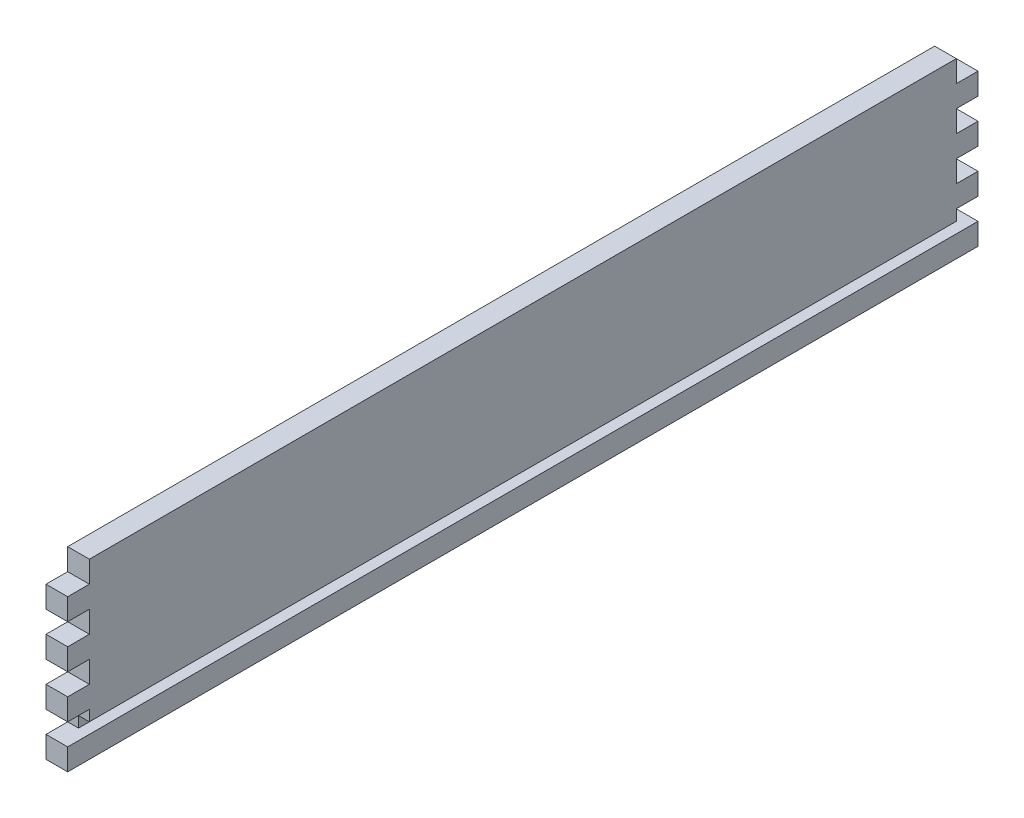
SolidWorks part; units mm, degrees
ref_plane "Front Plane" through (0, 0, 0) normal (0, 0, 1) x (1, 0, 0)
ref_plane "Top Plane" through (0, 0, 0) normal (0, 1, 0) x (1, 0, 0)
ref_plane "Right Plane" through (0, 0, 0) normal (1, 0, 0) x (0, 0, -1)
sketch "Sketch1" plane through (0, 0, 0) normal (1, 0, 0) x (0, 0, -1)
  line L0 (12.7, 101.6) -> (12.7, 88.9)
  line L1 (0, 0) -> (533.4, 0)
  line L2 (0, 0) -> (0, 12.7)
  line L3 (12.7, 101.6) -> (520.7, 101.6)
  line L4 (533.4, 0) -> (533.4, 12.7)
  line L5 (12.7, 88.9) -> (0, 88.9)
  line L6 (12.7, 76.2) -> (0, 76.2)
  line L8 (12.7, 63.5) -> (0, 63.5)
  line L9 (12.7, 76.2) -> (12.7, 63.5)
  line L10 (12.7, 50.8) -> (0, 50.8)
  line L12 (12.7, 38.1) -> (0, 38.1)
  line L13 (12.7, 50.8) -> (12.7, 38.1)
  line L14 (12.7, 25.4) -> (0, 25.4)
  line L16 (12.7, 12.7) -> (0, 12.7)
  line L17 (12.7, 25.4) -> (12.7, 12.7)
  line L18 (12.7, 0) -> (0, 0)
  line L20 (0, 76.2) -> (0, 88.9)
  line L21 (0, 50.8) -> (0, 63.5)
  line L22 (0, 25.4) -> (0, 38.1)
  line L23 (520.7, 101.6) -> (520.7, 88.9)
  line L24 (520.7, 88.9) -> (533.4, 88.9)
  line L26 (520.7, 76.2) -> (533.4, 76.2)
  line L27 (520.7, 76.2) -> (520.7, 63.5)
  line L28 (520.7, 63.5) -> (533.4, 63.5)
  line L30 (520.7, 50.8) -> (533.4, 50.8)
  line L31 (520.7, 50.8) -> (520.7, 38.1)
  line L32 (520.7, 38.1) -> (533.4, 38.1)
  line L34 (520.7, 25.4) -> (533.4, 25.4)
  line L35 (520.7, 25.4) -> (520.7, 12.7)
  line L36 (520.7, 12.7) -> (533.4, 12.7)
  line L38 (520.7, 0) -> (533.4, 0)
  line L39 (533.4, 76.2) -> (533.4, 88.9)
  line L40 (533.4, 50.8) -> (533.4, 63.5)
  line L41 (533.4, 25.4) -> (533.4, 38.1)
  line L42 (12.7, 88.9) -> (12.7, 76.2) [skipped]
  line L43 (12.7, 63.5) -> (12.7, 50.8) [skipped]
  line L44 (12.7, 38.1) -> (12.7, 25.4) [skipped]
  line L45 (12.7, 12.7) -> (12.7, 0) [skipped]
  line L46 (520.7, 88.9) -> (520.7, 76.2) [skipped]
  line L47 (520.7, 63.5) -> (520.7, 50.8) [skipped]
  line L48 (520.7, 38.1) -> (520.7, 25.4) [skipped]
  line L49 (520.7, 12.7) -> (520.7, 0) [skipped]
  dimension "D1" = 533.4
  dimension "D2" = 101.6
  dimension "D3" = 12.7
  dimension "D4" = 12.7
  dimension "D6" = 12.7
  dimension "D7" = 12.7
  dimension "D5" = 8
  dimension "D8" = 8
extrude "Boss-Extrude1" add sketch "Sketch1" along normal blind 12.7 contours L34 L41 L32 L31 L30 L40 L28 L27 L26 L39 L24 L23 L3 L0 L5 L20 L6 L9 L8 L21 L10 L13 L12 L22 L14 L17 L16 L2 L1 L4 L36 L35
sketch "Sketch2" plane through (12.7, 0, 0) normal (1, 0, 0) x (0, 0, -1)
  line L0 (0, 0) -> (533.4, 0) construction
  line L1 (-10.8368, 19.05) -> (568.3984, 19.05)
  line L2 (-10.8368, 19.05) -> (-10.8368, 12.7)
  line L3 (-10.8368, 12.7) -> (568.3984, 12.7)
  line L4 (568.3984, 19.05) -> (568.3984, 12.7)
  dimension "D1" = 12.7
  dimension "D2" = 6.35
extrude "Cut-Extrude1" cut sketch "Sketch2" against normal blind 6.35
